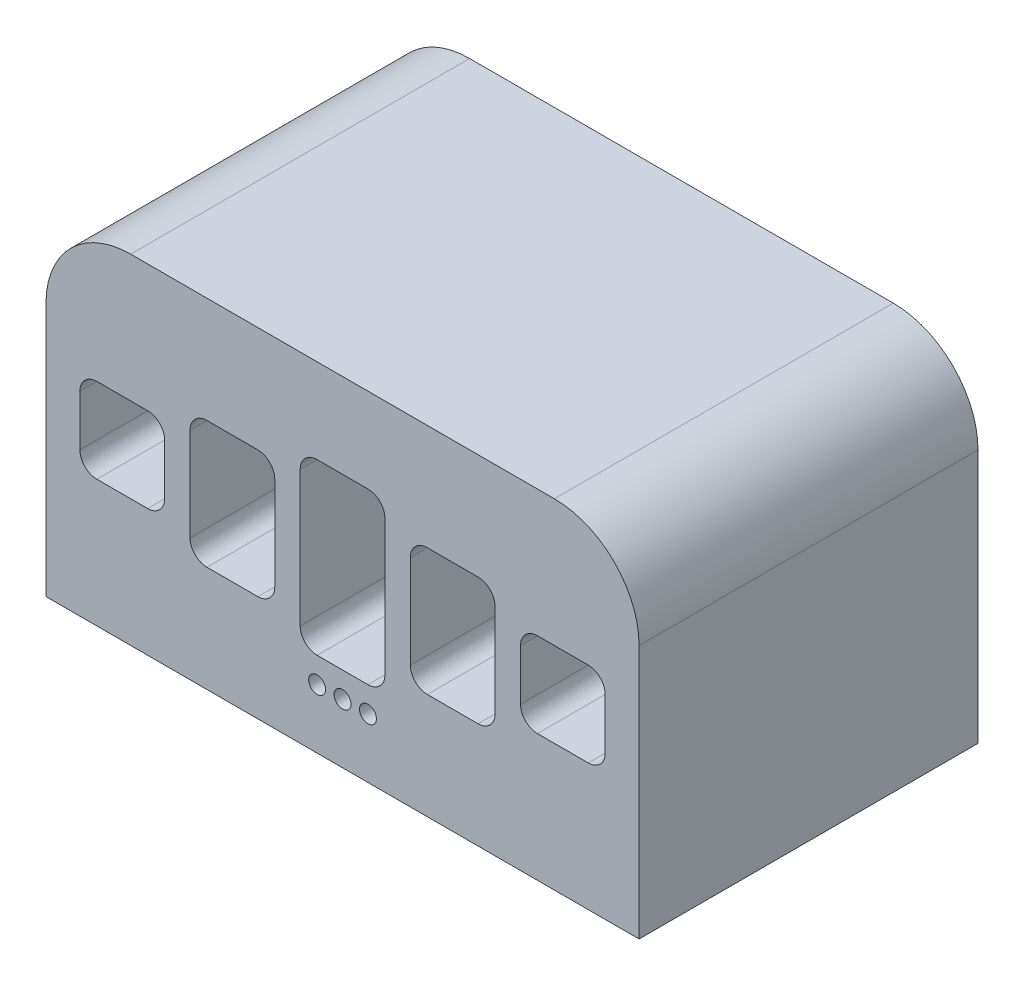
SolidWorks part; units mm, degrees
ref_plane "Front Plane" through (0, 0, 0) normal (0, 0, 1) x (1, 0, 0)
ref_plane "Top Plane" through (0, 0, 0) normal (0, 1, 0) x (1, 0, 0)
ref_plane "Right Plane" through (0, 0, 0) normal (1, 0, 0) x (0, 0, -1)
sketch "Sketch1" plane through (0, 0, 0) normal (0, 0, 1) x (1, 0, 0)
  line L1 (0, 0) -> (70, 0)
  line L2 (0, 0) -> (0, 40)
  line L3 (0, 40) -> (70, 40)
  line L4 (70, 0) -> (70, 40)
extrude "Boss-Extrude1" add sketch "Sketch1" along normal blind 40
sketch "Sketch2" plane through (0, 0, 40) normal (0, 0, 1) x (1, 0, 0)
  line L3 (30, 20) -> (30, 30)
  line L4 (30, 30) -> (40, 30)
  line L5 (40, 30) -> (40, 20)
  line L6 (30, 20) -> (30, 10)
  line L7 (30, 10) -> (40, 10)
  line L8 (40, 10) -> (40, 20)
extrude "Cut-Extrude1" cut sketch "Sketch2" against normal blind 10
sketch "Sketch3" plane through (0, 0, 40) normal (0, 0, 1) x (1, 0, 0)
  line L0 (27, 12.5) -> (17, 12.5)
  line L2 (17, 12.5) -> (17, 27.5)
  line L3 (27, 15) -> (27, 12.5)
  line L4 (27, 15) -> (27, 27.5)
  line L5 (17, 27.5) -> (27, 27.5)
extrude "Cut-Extrude2" cut sketch "Sketch3" against normal blind 10
sketch "Sketch4" plane through (0, 0, 40) normal (0, 0, 1) x (1, 0, 0)
  line L0 (43, 25) -> (43, 27.5)
  line L2 (43, 27.5) -> (53, 27.5)
  line L3 (43, 12.5) -> (43, 25)
  line L4 (53, 27.5) -> (53, 12.5)
  line L5 (53, 12.5) -> (43, 12.5)
extrude "Cut-Extrude3" cut sketch "Sketch4" against normal blind 10
sketch "Sketch5" plane through (0, 0, 40) normal (0, 0, 1) x (1, 0, 0)
  line L3 (14, 25) -> (4, 25)
  line L4 (4, 25) -> (4, 15)
  line L5 (4, 15) -> (14, 15)
  line L6 (14, 15) -> (14, 25)
extrude "Cut-Extrude4" cut sketch "Sketch5" against normal blind 10
sketch "Sketch6" plane through (0, 0, 40) normal (0, 0, 1) x (1, 0, 0)
  line L3 (56, 25) -> (56, 15)
  line L4 (56, 15) -> (66, 15)
  line L5 (66, 15) -> (66, 25)
  line L6 (66, 25) -> (56, 25)
extrude "Cut-Extrude5" cut sketch "Sketch6" against normal blind 10
fillet "Fillet21" radius 2 20 edges at (4, 15, 35) (14, 15, 35) (17, 12.5, 35) (27, 12.5, 35) (30, 10, 35) (40, 10, 35) (43, 12.5, 35) (66, 15, 35) (56, 15, 35) (53, 12.5, 35) (53, 27.5, 35) (27, 27.5, 35) (14, 25, 35) (17, 27.5, 35) (66, 25, 35) (56, 25, 35) (43, 27.5, 35) (40, 30, 35) (30, 30, 35) (4, 25, 35)
fillet "Fillet22" radius 10 2 edges at (70, 40, 20) (0, 40, 20)
sketch "Sketch7" plane through (0, 0, 40) normal (0, 0, 1) x (1, 0, 0)
  circle A0 centre (32, 7) radius 1
  circle A1 centre (35, 7) radius 1
  circle A2 centre (38, 7) radius 1
extrude "Cut-Extrude6" cut sketch "Sketch7" against normal blind 10
